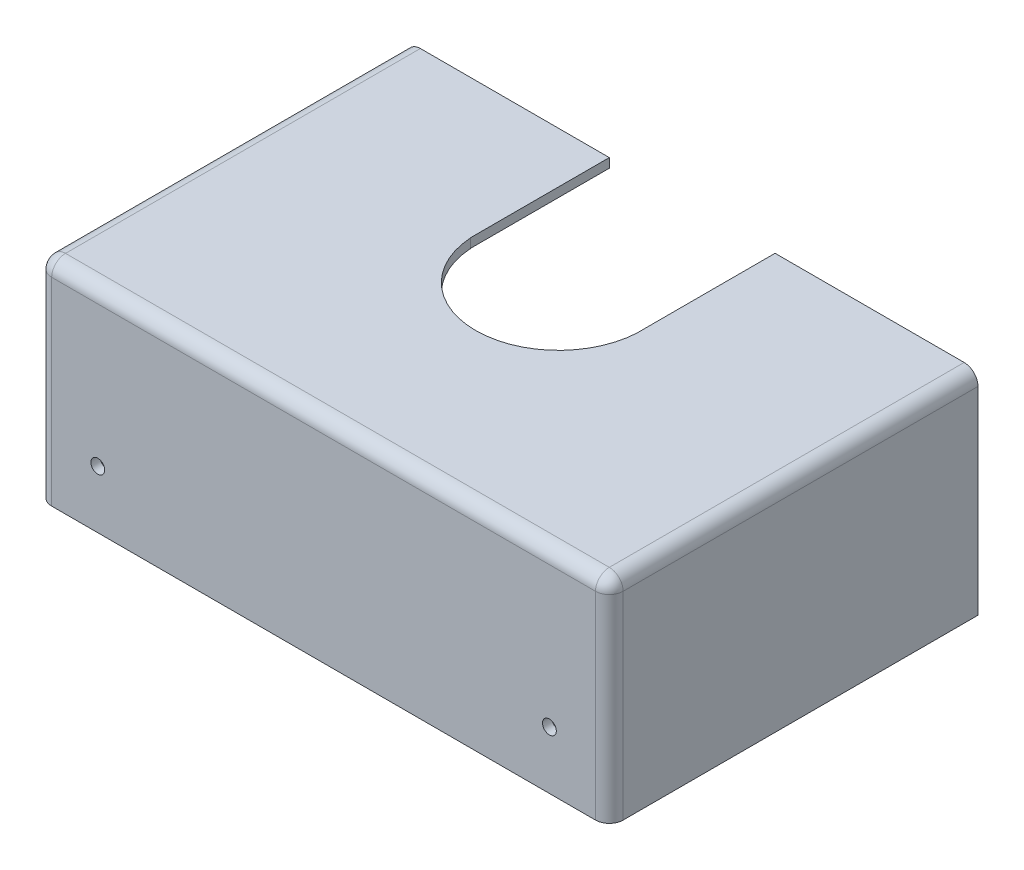
SolidWorks part; units mm, degrees
ref_plane "Front Plane" through (0, 0, 0) normal (0, 0, 1) x (1, 0, 0)
ref_plane "Top Plane" through (0, 0, 0) normal (0, 1, 0) x (1, 0, 0)
ref_plane "Right Plane" through (0, 0, 0) normal (1, 0, 0) x (0, 0, -1)
sketch "Sketch1" plane through (0, 0, 0) normal (0, 0, 1) x (1, 0, 0)
  line L1 (0, 0) -> (124, 0)
  line L2 (0, 0) -> (0, 46)
  line L3 (0, 46) -> (124, 46)
  line L4 (124, 0) -> (124, 46)
  dimension "D1" = 124
  dimension "D2" = 46
extrude "Boss-Extrude1" add sketch "Sketch1" along normal blind 80
sketch "Sketch2" plane through (0, 0, 0) normal (0, 0, -1) x (-1, 0, 0)
  line L0 (0, 0) -> (-124, 0) construction
  line L1 (-122, 0) -> (-2, 0)
  line L2 (-122, 0) -> (-122, 44)
  line L3 (-122, 44) -> (-2, 44)
  line L4 (-2, 0) -> (-2, 44)
  line L5 (-124, 0) -> (-124, 46) construction
  line L6 (-124, 46) -> (0, 46) construction
  line L7 (0, 46) -> (0, 0) construction
  dimension "D1" = 2
  dimension "D2" = 2
  dimension "D3" = 2
extrude "Cut-Extrude1" cut sketch "Sketch2" against normal blind 78
sketch "Sketch3" plane through (0, 46, 0) normal (0, 1, 0) x (1, 0, 0)
  line L0 (124, -80) -> (124, 0) construction
  line L1 (124, 0) -> (0, 0) construction
  circle A0 centre (62, -29) radius 18
  dimension "D1" = 36
  dimension "D2" = 62
  dimension "D3" = 29
extrude "Cut-Extrude2" cut sketch "Sketch3" against normal blind 78
sketch "Sketch4" plane through (0, 46, 0) normal (0, 1, 0) x (1, 0, 0)
  line L0 (124, 0) -> (0, 0) construction
  line L1 (79.9644, -30.1318) -> (44, -30.1318)
  line L2 (79.9644, -30.1318) -> (79.9644, 0)
  line L3 (79.9644, 0) -> (44, 0)
  line L4 (44, -30.1318) -> (44, 0)
  circle A0 centre (62, -29) radius 18 construction
extrude "Cut-Extrude3" cut sketch "Sketch4" against normal blind 78
fillet "Fillet1" radius 1 3 edges at (2, 22, 78) (2, 44, 39) (62, 44, 78)
fillet "Fillet2" radius 1 3 edges at (122, 43.7071, 77.7071) (122, 21.5, 78) (122, 44, 38.5)
fillet "Fillet3" radius 3 5 edges at (0, 23, 80) (0, 46, 40) (124, 23, 80) (62, 46, 80) (124, 46, 40)
hole_wizard "Ø3.0mm Dowel Hole1" positions "3DSketch1" profile "Sketch5" hole size "Ø3.0" standard "ISO" end condition through all
sketch3d "3DSketch1"
  line L0 (3, 0, 80) -> (121, 0, 80) construction
  line L1 (3, 43, 80) -> (3, 0, 80) construction
  line L2 (121, 0, 80) -> (121, 43, 80) construction
  point P0 (13, 12.5, 80)
  point P2 (111, 12.5, 80)
  dimension "D1" = 12.5
  dimension "D2" = 10
  dimension "D3" = 10
  dimension "D4" = 12.5
sketch "Sketch5" plane through (13, 12.5, 80) normal (1, 0, 0) x (0, -1, 0)
  line L0 (0, 0) -> (0, 80)
  line L1 (0, 80) -> (1.5, 80)
  line L2 (1.5, 80) -> (1.5, 0)
  line L5 (1.5, 0) -> (0, 0)
  line L11 (0, -6.35) -> (0, 107.95) construction
  dimension "Thru Hole Dia." = 3
  dimension "Thru Hole Depth" = 80
